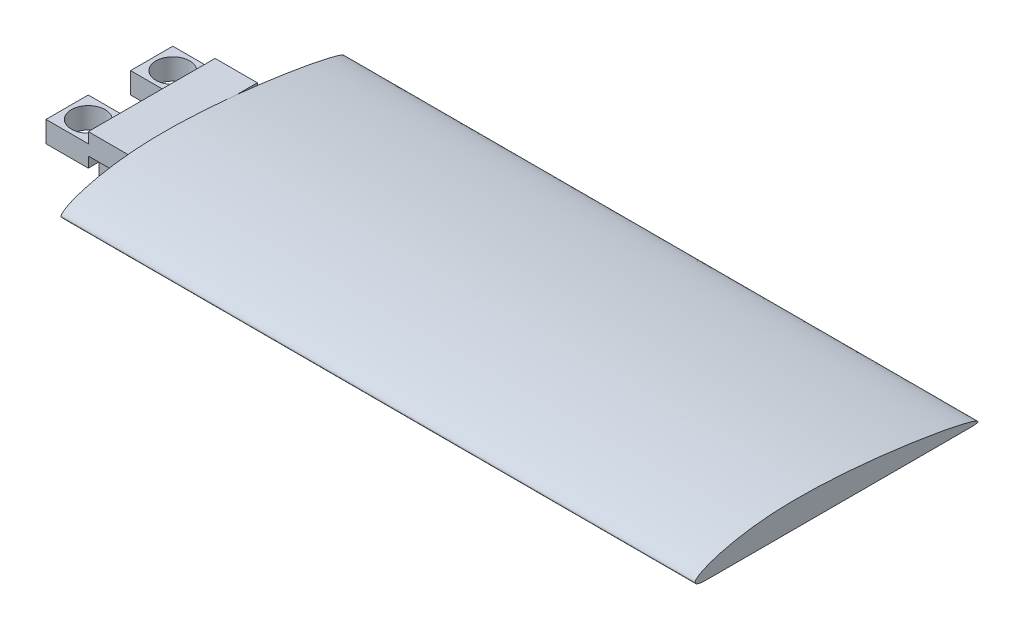
SolidWorks part; units mm, degrees
ref_plane "Front Plane" through (0, 0, 0) normal (0, 0, 1) x (1, 0, 0)
ref_plane "Top Plane" through (0, 0, 0) normal (0, 1, 0) x (1, 0, 0)
ref_plane "Right Plane" through (0, 0, 0) normal (1, 0, 0) x (0, 0, -1)
sketch "Sketch1" plane through (0, 0, 0) normal (0, 1, 0) x (1, 0, 0)
  line L0 (0, 5) -> (10, -5) construction
  line L5 (0, 5) -> (10, 5)
  line L6 (0, 5) -> (0, -5)
  line L7 (0, -5) -> (10, -5)
  line L8 (10, 5) -> (10, -5)
  line L9 (0, -5) -> (10, 5) construction
  line L10 (-2.6397, 10) -> (16.4497, 10) construction
  line L11 (0, 25) -> (10, 15) construction
  line L12 (0, 15) -> (10, 25) construction
  line L13 (10, 15) -> (10, 25)
  line L14 (0, 25) -> (10, 25)
  line L15 (0, 15) -> (0, 25)
  line L16 (0, 15) -> (10, 15)
  circle A0 centre (5, 0) radius 4
  circle A1 centre (5, 20) radius 4
  point P0 (0, 0)
  dimension "D2" = 5
  dimension "D1" = 10
extrude "Boss-Extrude1" add sketch "Sketch1" along normal blind 5
sketch "Sketch2" plane through (10, 0, 0) normal (1, 0, 0) x (0, 0, -1)
  line L0 (-5, 5) -> (5, 5) construction
  line L1 (-2.5, -5) -> (2.5, -5)
  line L2 (-2.5, -5) -> (-2.5, 5)
  line L3 (-2.5, 5) -> (2.5, 5)
  line L4 (2.5, -5) -> (2.5, 5)
  line L5 (-2.5, -5) -> (2.5, 5) construction
  line L6 (-2.5, 5) -> (2.5, -5) construction
  line L7 (15, 0) -> (25, 0) construction
  line L8 (15, 5) -> (25, 5) construction
  line L9 (17.5, -5) -> (22.5, -5)
  line L10 (17.5, -5) -> (17.5, 5)
  line L11 (17.5, 5) -> (22.5, 5)
  line L12 (22.5, -5) -> (22.5, 5)
  line L13 (17.5, -5) -> (22.5, 5) construction
  line L14 (17.5, 5) -> (22.5, -5) construction
  point P0 (0, 0)
  point P10 (20, 0)
  dimension "D1" = 5
extrude "Boss-Extrude2" add sketch "Sketch2" along normal blind 5
sketch "Sketch4" plane through (0, 5, 0) normal (0, 1, 0) x (1, 0, 0)
  line L10 (10, 25) -> (20, 25)
  line L11 (10, 25) -> (10, -5)
  line L12 (10, -5) -> (20, -5)
  line L13 (20, 25) -> (20, -5)
extrude "Boss-Extrude4" add sketch "Sketch4" along normal mid plane 5
sketch "Sketch6" plane through (20, 0, 0) normal (1, 0, 0) x (0, 0, -1)
  line L0 (-18.539, 2.5) -> (43.5819, 2.5)
  line L1 (-5, 2.5) -> (25, 2.5) construction
  line L2 (42.2751, 2.5) -> (44.8886, 2.5) construction
  line L3 (-23.216, 2.5) -> (-13.862, 2.5) construction
  spline S0 degree 3 poles (-18.539, 2.5) (-26.2287, 2.5) (-5.8215, 14.5378) (54.1094, 2.5) (43.5819, 2.5) knots 0 0 0 0 0.416526 1 1 1 1
extrude "Boss-Extrude6" add sketch "Sketch6" along normal blind 150
